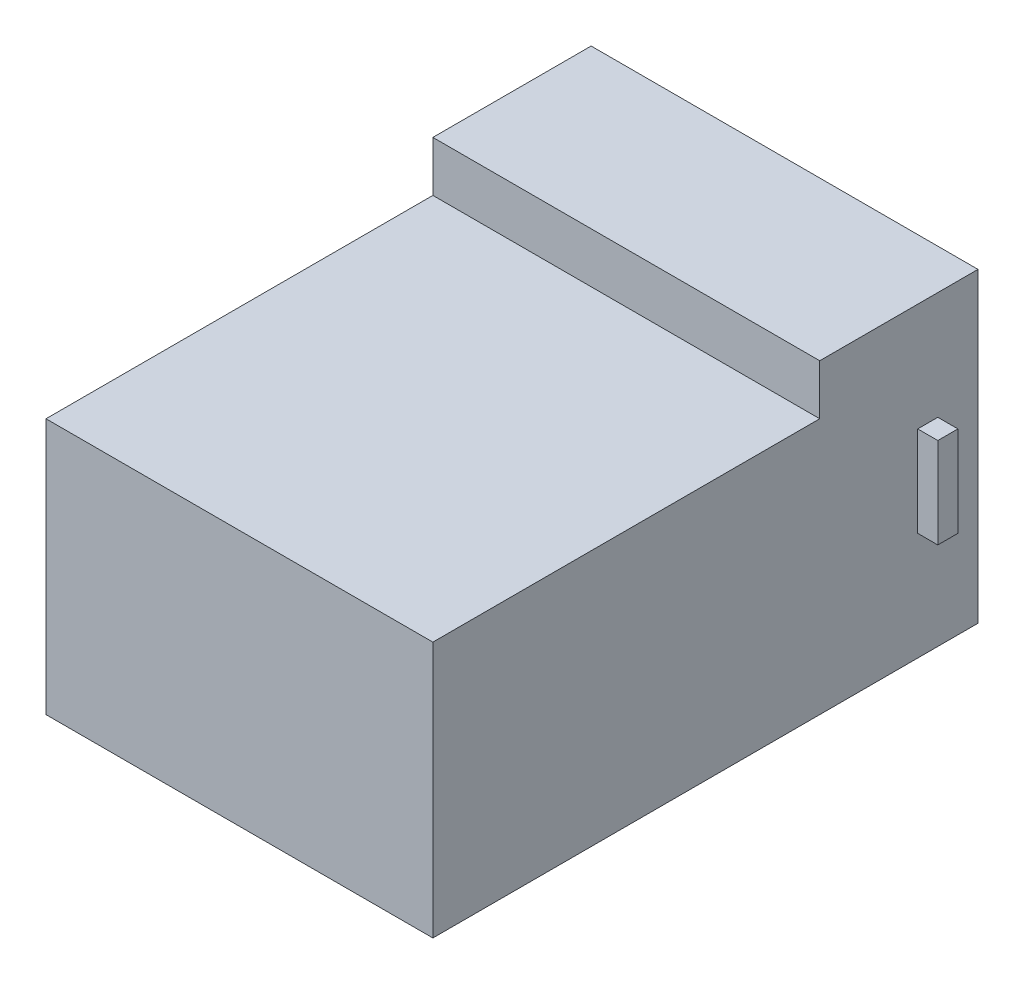
SolidWorks part; units mm, degrees
ref_plane "前视基准面" through (0, 0, 0) normal (0, 0, 1) x (1, 0, 0)
ref_plane "上视基准面" through (0, 0, 0) normal (0, 1, 0) x (1, 0, 0)
ref_plane "右视基准面" through (0, 0, 0) normal (1, 0, 0) x (0, 0, -1)
other "Configuration Table"
sketch "草图1" plane through (0, 0, 0) normal (0, 0, 1) x (1, 0, 0)
  line L1 (0, 0) -> (77, 0)
  line L2 (0, 0) -> (0, 61)
  line L3 (0, 61) -> (77, 61)
  line L4 (77, 0) -> (77, 61)
  dimension "D1" = 61
  dimension "D2" = 77
extrude "凸台-拉伸1" add sketch "草图1" along normal blind 108.5
sketch "草图2" plane through (0, 61, 0) normal (0, 1, 0) x (1, 0, 0)
  line L0 (77, -108.5) -> (77, 0) construction
  line L1 (0, -108.5) -> (77, -108.5)
  line L2 (0, -108.5) -> (0, -31.5)
  line L3 (0, -31.5) -> (77, -31.5)
  line L4 (77, -108.5) -> (77, -31.5)
  dimension "D1" = 77
extrude "切除-拉伸1" cut sketch "草图2" against normal blind 10
ref_plane "基准面1" through (0, 21.5, 0) normal (0, -1, 0) x (-1, 0, 0)
sketch "草图3" plane through (0, 21.5, 0) normal (0, -1, 0) x (-1, 0, 0)
  line L0 (-77, 0) -> (0, 0) construction
  line L1 (4, -8) -> (-81, -8)
  line L2 (4, -8) -> (4, -12)
  line L3 (4, -12) -> (-81, -12)
  line L4 (-81, -8) -> (-81, -12)
  line L5 (0, -108.5) -> (0, 0) construction
  line L6 (-77, -108.5) -> (-77, 0) construction
  dimension "D1" = 8
  dimension "D2" = 12
  dimension "D3" = 4
  dimension "D4" = 4
extrude "凸台-拉伸2" add sketch "草图3" against normal offset from surface (18 mm away) 21.5 up to face at (38.5, 61, 15.75)
